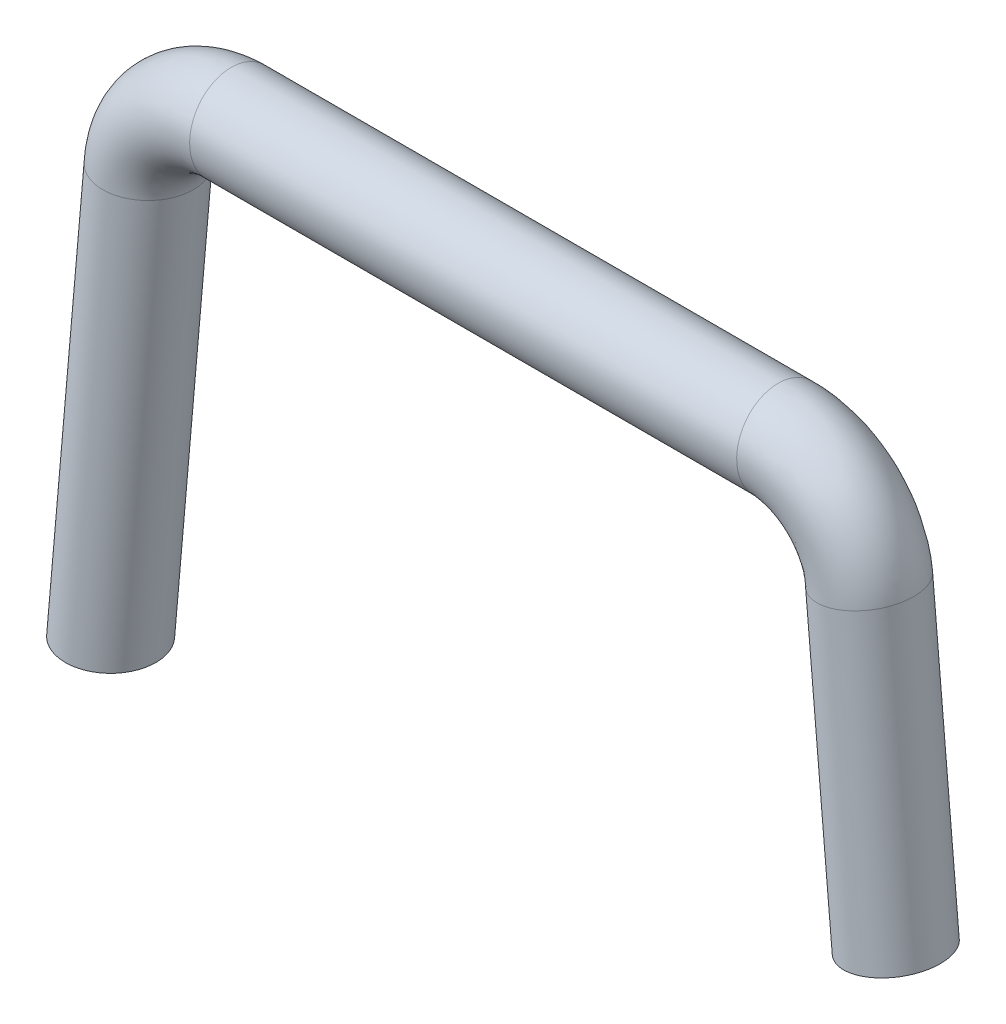
SolidWorks part; units mm, degrees
material "Alloy Steel"
ref_plane "Front Plane" through (0, 0, 0) normal (0, 0, 1) x (1, 0, 0)
ref_plane "Top Plane" through (0, 0, 0) normal (0, 1, 0) x (1, 0, 0)
ref_plane "Right Plane" through (0, 0, 0) normal (1, 0, 0) x (0, 0, -1)
sketch "Circle" plane through (0, 0, 0) normal (0, 0, 1) x (1, 0, 0)
  line L0 (0, 0) -> (5.7897, 66.1766)
  line L1 (19.2383, 78.5) -> (103.7827, 78.5)
  line L2 (117.2313, 66.1766) -> (121.35, 19.1)
  line L3 (0, 0) -> (0, 133.1903) construction
  arc A0 (5.7897, 66.1766) -> (19.2383, 78.5) centre (19.2383, 65) cw
  arc A1 (103.7827, 78.5) -> (117.2313, 66.1766) centre (103.7827, 65) cw
  dimension "D1" = 13.5
  dimension "D3" = 121.35
  dimension "D2" = 78.5
  dimension "D4" = 10
  dimension "D5" = 59.4
  dimension "D6" = 5
sketch "Path" plane through (0, 0, 0) normal (0, 1, 0) x (1, 0, 0)
  circle A0 centre (0, 0) radius 7
  dimension "D1" = 14
sweep "Cam Handle" add profiles "Path" path "Circle"
